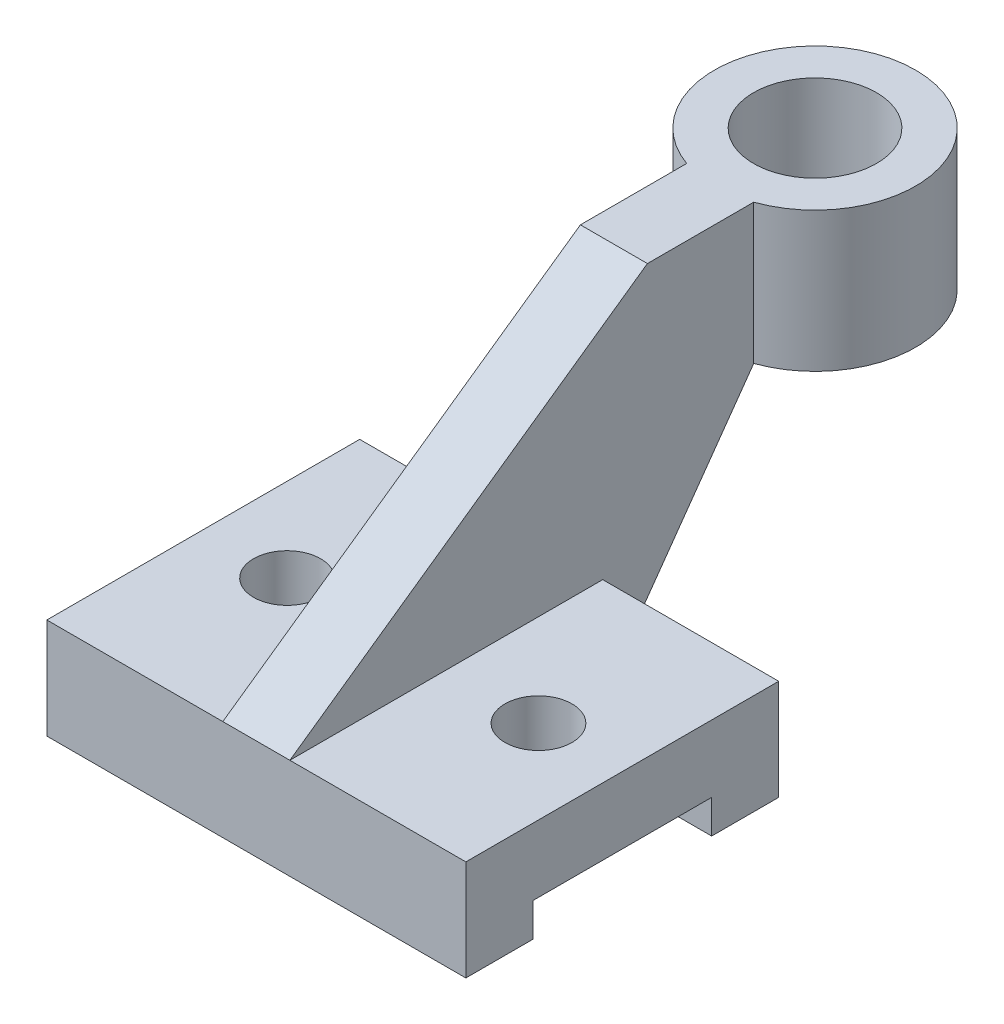
SolidWorks part; units mm, degrees
ref_plane "Plan de face" through (0, 0, 0) normal (0, 0, 1) x (1, 0, 0)
ref_plane "Plan de dessus" through (0, 0, 0) normal (0, 1, 0) x (1, 0, 0)
ref_plane "Plan de droite" through (0, 0, 0) normal (1, 0, 0) x (0, 0, -1)
sketch "Esquisse4" plane through (0, 0, 0) normal (0, 1, 0) x (1, 0, 0)
  line L1 (-37.5, -28) -> (37.5, -28)
  line L2 (-37.5, -28) -> (-37.5, 28)
  line L3 (-37.5, 28) -> (37.5, 28)
  line L4 (37.5, -28) -> (37.5, 28)
  line L5 (-37.5, -28) -> (37.5, 28) construction
  line L6 (-37.5, 28) -> (37.5, -28) construction
  point P0 (0, 0)
  dimension "D1" = 75
  dimension "D2" = 56
extrude "Boss.-Extru.2" add sketch "Esquisse4" along normal blind 18
sketch "Esquisse5" plane through (0, 18, 0) normal (0, 1, 0) x (1, 0, 0)
  line L0 (37.5, -28) -> (37.5, 28) construction
  line L1 (37.5, 28) -> (-37.5, 28) construction
  circle A0 centre (22.5, 0) radius 6
  dimension "D2" = 28
  dimension "D3" = 12
  dimension "D1" = 15
extrude "Enlèv. mat.-Extru.3" cut sketch "Esquisse5" against normal through all
mirror "Symétrie1" about plane through (0, 0, 0) normal (1, 0, 0) of "Enlèv. mat.-Extru.3"
sketch "Esquisse6" plane through (37.5, 0, 0) normal (1, 0, 0) x (0, 0, -1)
  line L0 (-16, 0) -> (-16, 6)
  line L1 (-16, 0) -> (16, 0)
  line L2 (-16, 6) -> (16, 6)
  line L3 (16, 0) -> (16, 6)
  line L4 (-28, 0) -> (28, 0) construction
  line L5 (0, 0) -> (0, 9.7985) construction
  dimension "D1" = 6
  dimension "D2" = 32
extrude "Enlèv. mat.-Extru.4" cut sketch "Esquisse6" against normal through all
ref_plane "Plan2" through (0, 63, 0) normal (0, -1, 0) x (-1, 0, 0)
sketch "Esquisse9" plane through (0, 63, 0) normal (0, -1, 0) x (-1, 0, 0)
  line L0 (37.5, -28) -> (-37.5, -28) construction
  circle A0 centre (0, 72) radius 18
  circle A1 centre (0, 72) radius 11
  point P3 (0, 0)
  dimension "D1" = 36
  dimension "D2" = 22
  dimension "D3" = 100
extrude "Boss.-Extru.3" add sketch "Esquisse9" along normal blind 25 separate body
ref_plane "Plan3" through (0, 0, -36) normal (0, 0, 1) x (1, 0, 0)
sketch "Esquisse10" plane through (0, 0, -36) normal (0, 0, 1) x (1, 0, 0)
  line L0 (-6, 63) -> (-6, 38)
  line L1 (-6, 63) -> (6, 63)
  line L2 (-6, 38) -> (6, 38)
  line L3 (6, 63) -> (6, 38)
  line L4 (-6.6, 63) -> (6.6, 63) construction
  line L5 (0, 0) -> (0, 52.7012) construction
  dimension "D1" = 12
  dimension "D2" = 25
extrude "Boss.-Extru.6" add sketch "Esquisse10" against normal up to next
sketch "Esquisse11" plane through (0, 0, 0) normal (1, 0, 0) x (0, 0, -1)
  line L0 (36, 63) -> (-28, 18)
  line L1 (28, 0) -> (55.0294, 38)
  line L2 (28, 18) -> (28, 0) construction
  line L3 (-28, 18) -> (28, 18) construction
  line L4 (28, 18) -> (28, 0)
  line L5 (-28, 18) -> (28, 18)
  line L6 (55.0294, 38) -> (36, 38) construction
  line L7 (36, 38) -> (36, 63) construction
  line L8 (55.0294, 38) -> (36, 38)
  line L9 (36, 38) -> (36, 63)
extrude "Boss.-Extru.7" add sketch "Esquisse11" along normal mid plane 12
